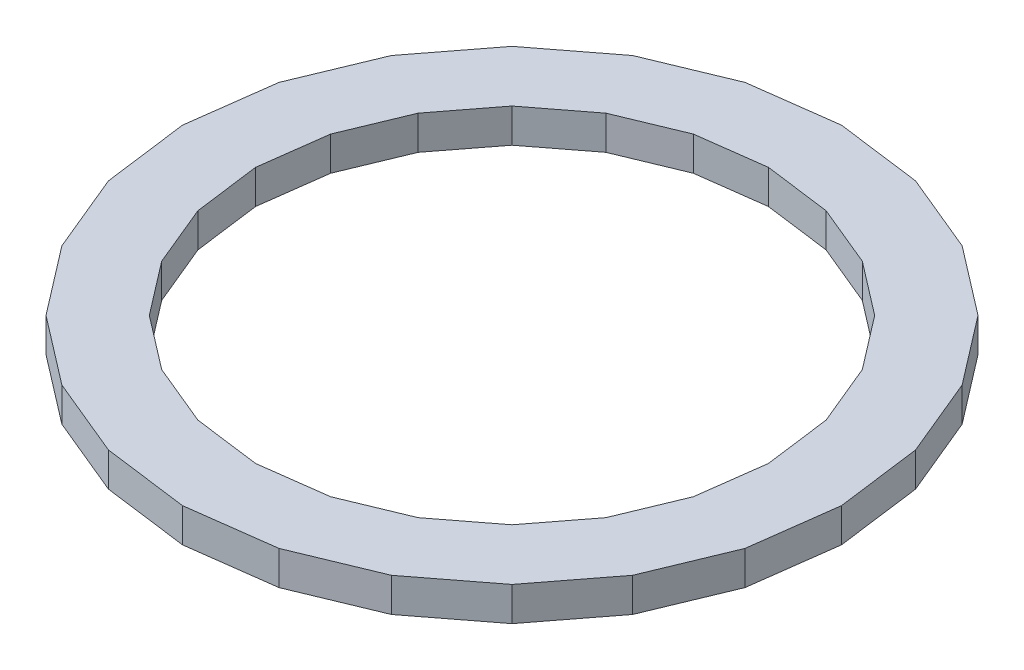
SolidWorks part; units mm, degrees
ref_plane "Front Plane" through (0, 0, 0) normal (0, 0, 1) x (1, 0, 0)
ref_plane "Top Plane" through (0, 0, 0) normal (0, 1, 0) x (1, 0, 0)
ref_plane "Right Plane" through (0, 0, 0) normal (1, 0, 0) x (0, 0, -1)
sketch "Sketch2" plane through (0, 0, 0) normal (0, 1, 0) x (1, 0, 0)
  line L0 (0, 0) -> (-143.8764, 0) construction
  line L1 (-184.8671, 0) -> (-178.5679, -47.8471)
  line L2 (-178.5679, -47.8471) -> (-160.0996, -92.4336)
  line L3 (-160.0996, -92.4336) -> (-130.7208, -130.7208)
  line L4 (-130.7208, -130.7208) -> (-92.4336, -160.0996)
  line L5 (-92.4336, -160.0996) -> (-47.8471, -178.5679)
  line L6 (-47.8471, -178.5679) -> (0, -184.8671)
  line L7 (0, -184.8671) -> (47.8471, -178.5679)
  line L8 (47.8471, -178.5679) -> (92.4336, -160.0996)
  line L9 (92.4336, -160.0996) -> (130.7208, -130.7208)
  line L10 (130.7208, -130.7208) -> (160.0996, -92.4336)
  line L11 (160.0996, -92.4336) -> (178.5679, -47.8471)
  line L12 (178.5679, -47.8471) -> (184.8671, 0)
  line L13 (184.8671, 0) -> (178.5679, 47.8471)
  line L14 (178.5679, 47.8471) -> (160.0996, 92.4336)
  line L15 (160.0996, 92.4336) -> (130.7208, 130.7208)
  line L16 (130.7208, 130.7208) -> (92.4336, 160.0996)
  line L17 (92.4336, 160.0996) -> (47.8471, 178.5679)
  line L18 (47.8471, 178.5679) -> (0, 184.8671)
  line L19 (0, 184.8671) -> (-47.8471, 178.5679)
  line L20 (-47.8471, 178.5679) -> (-92.4336, 160.0996)
  line L21 (-92.4336, 160.0996) -> (-130.7208, 130.7208)
  line L22 (-130.7208, 130.7208) -> (-160.0996, 92.4336)
  line L23 (-160.0996, 92.4336) -> (-178.5679, 47.8471)
  line L24 (-178.5679, 47.8471) -> (-184.8671, 0)
  line L25 (-143.8764, 0) -> (-138.974, -37.238)
  line L26 (-138.974, -37.238) -> (-124.6006, -71.9382)
  line L27 (-124.6006, -71.9382) -> (-101.736, -101.736)
  line L28 (-101.736, -101.736) -> (-71.9382, -124.6006)
  line L29 (-71.9382, -124.6006) -> (-37.238, -138.974)
  line L30 (-37.238, -138.974) -> (0, -143.8764)
  line L31 (0, -143.8764) -> (37.238, -138.974)
  line L32 (37.238, -138.974) -> (71.9382, -124.6006)
  line L33 (71.9382, -124.6006) -> (101.736, -101.736)
  line L34 (101.736, -101.736) -> (124.6006, -71.9382)
  line L35 (124.6006, -71.9382) -> (138.974, -37.238)
  line L36 (138.974, -37.238) -> (143.8764, 0)
  line L37 (143.8764, 0) -> (138.974, 37.238)
  line L38 (138.974, 37.238) -> (124.6006, 71.9382)
  line L39 (124.6006, 71.9382) -> (101.736, 101.736)
  line L40 (101.736, 101.736) -> (71.9382, 124.6006)
  line L41 (71.9382, 124.6006) -> (37.238, 138.974)
  line L42 (37.238, 138.974) -> (0, 143.8764)
  line L43 (0, 143.8764) -> (-37.238, 138.974)
  line L44 (-37.238, 138.974) -> (-71.9382, 124.6006)
  line L45 (-71.9382, 124.6006) -> (-101.736, 101.736)
  line L46 (-101.736, 101.736) -> (-124.6006, 71.9382)
  line L47 (-124.6006, 71.9382) -> (-138.974, 37.238)
  line L48 (-138.974, 37.238) -> (-143.8764, 0)
  line L49 (-184.8671, 0) -> (-143.8764, 0) construction
  circle A0 centre (0, 0) radius 183.2855 construction
  circle A1 centre (0, 0) radius 142.6455 construction
  dimension "D1" = 40.64
  dimension "D2" = 48.26
extrude "Boss-Extrude2" add sketch "Sketch2" along normal blind 19.05
